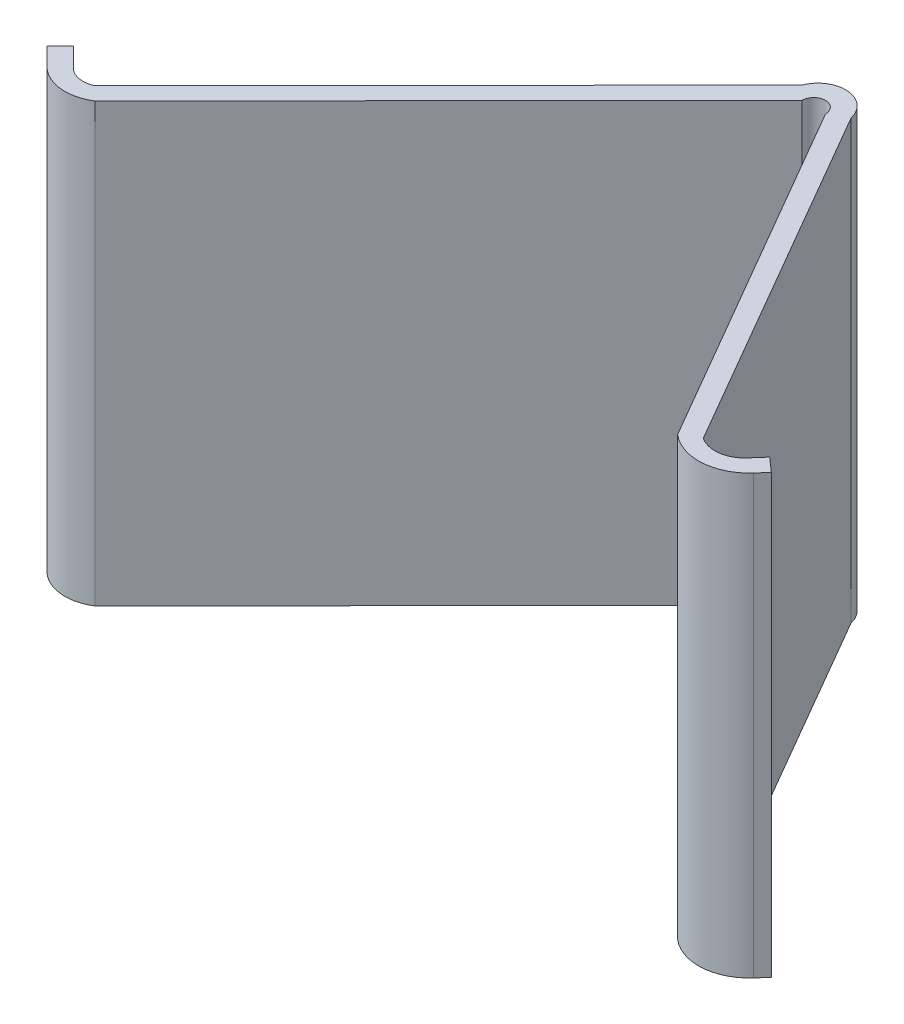
SolidWorks part; units mm, degrees
ref_plane "前基準面" through (0, 0, 0) normal (0, 0, 1) x (1, 0, 0)
ref_plane "上基準面" through (0, 0, 0) normal (0, 1, 0) x (1, 0, 0)
ref_plane "右基準面" through (0, 0, 0) normal (1, 0, 0) x (0, 0, -1)
sketch "草圖1" plane through (0, 0, 0) normal (0, 1, 0) x (1, 0, 0)
  line L0 (-45.4878, -38.6148) -> (10.9966, 18.0377)
  line L1 (-45.4878, -38.6148) -> (-43.3634, -40.733)
  line L2 (10.9966, 18.0377) -> (13.1211, 15.9196)
  line L3 (-43.3634, -40.733) -> (13.1211, 15.9196)
  line L4 (16.8986, 15.9196) -> (49.4822, -40.3237)
  line L5 (16.8986, 15.9196) -> (19.4945, 17.4234)
  line L6 (49.4822, -40.3237) -> (52.0781, -38.8199)
  line L7 (19.4945, 17.4234) -> (52.0781, -38.8199)
  line L8 (13.1211, 15.9196) -> (16.8986, 15.9196)
  line L9 (-52.0067, -39.7967) -> (-49.8886, -37.6722)
  line L10 (-52.0067, -39.7967) -> (-54.8394, -36.9725)
  line L11 (-49.8886, -37.6722) -> (-52.7212, -34.848)
  line L12 (-54.8394, -36.9725) -> (-52.7212, -34.848)
  line L17 (58.669, -37.6044) -> (59.9943, -36.1066)
  line L18 (58.669, -37.6044) -> (60.9158, -39.5924)
  line L19 (59.9943, -36.1066) -> (62.2411, -38.0946)
  line L20 (60.9158, -39.5924) -> (62.2411, -38.0946)
  arc A0 (18.3722, 13.3761) -> (11.3477, 14.141) centre (15.1528, 16.4481) ccw
  arc A1 (16.8986, 15.9196) -> (13.1211, 15.9196) centre (15.0098, 15.9196) ccw
  arc A2 (-43.3634, -40.733) -> (-52.0067, -39.7967) centre (-47.1014, -34.8768) cw
  arc A3 (-49.8886, -37.6722) -> (-45.4878, -38.6148) centre (-47.0796, -35.3018) ccw
  arc A4 (52.0781, -38.8199) -> (58.669, -37.6044) centre (54.7421, -34.788) ccw
  arc A5 (49.4822, -40.3237) -> (60.9158, -39.5924) centre (54.8313, -34.2087) ccw
  dimension "D1" = 3
  dimension "D2" = 3
  dimension "D3" = 3
  dimension "D4" = 2
  dimension "D5" = 75
  dimension "D6" = 80
  dimension "D7" = 65
  dimension "D8" = 90
  dimension "D9" = 4
  dimension "D10" = 3
extrude "填料-伸長1" add sketch "草圖1" along normal blind 70
